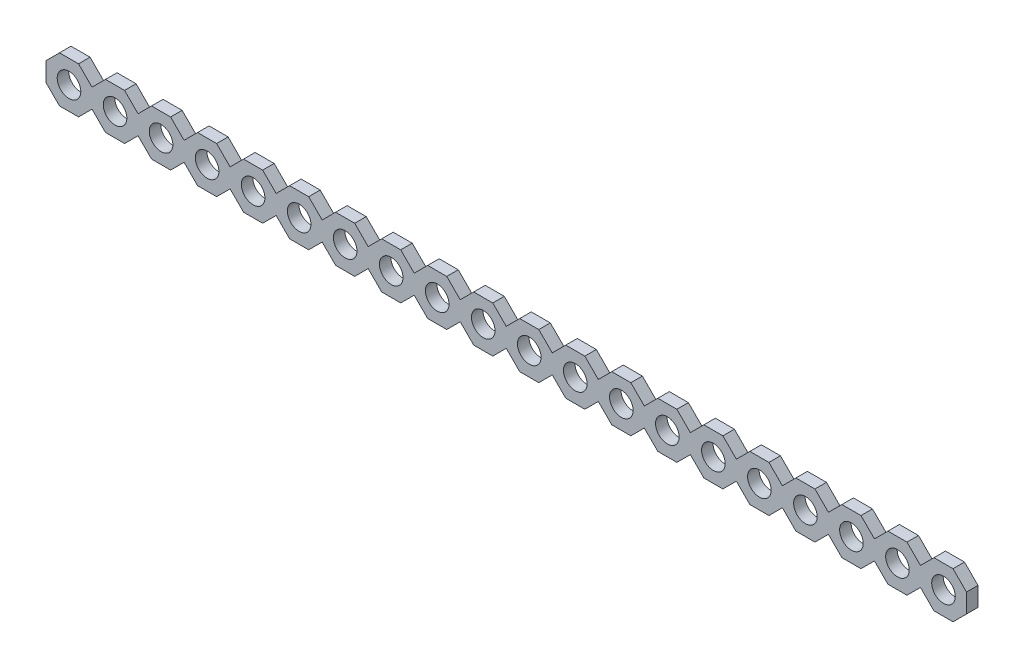
SolidWorks part; units mm, degrees
ref_plane "Front Plane" through (0, 0, 0) normal (0, 0, 1) x (1, 0, 0)
ref_plane "Top Plane" through (0, 0, 0) normal (0, 1, 0) x (1, 0, 0)
ref_plane "Right Plane" through (0, 0, 0) normal (1, 0, 0) x (0, 0, -1)
sketch "Sketch1" plane through (0, 0, 0) normal (0, 0, 1) x (1, 0, 0)
  line L1 (1.6569, 4) -> (-1.6569, 4)
  line L2 (-1.6569, 4) -> (-4, 1.6569)
  line L3 (-4, 1.6569) -> (-4, -1.6569)
  line L4 (-4, -1.6569) -> (-1.6569, -4)
  line L5 (-1.6569, -4) -> (1.6569, -4)
  line L6 (1.6569, -4) -> (4, -1.6569)
  line L7 (4, -1.6569) -> (4, 1.6569)
  line L8 (4, 1.6569) -> (1.6569, 4)
  circle A0 centre (0, 0) radius 4 construction
  circle A1 centre (0, 0) radius 2.05
  dimension "D2" = 4.1
  dimension "D1" = 8
extrude "Boss-Extrude1" add sketch "Sketch1" along normal blind 2
pattern_linear "LPattern1" count 20 spacing 8 along (1, 0, 0) of "Boss-Extrude1"
